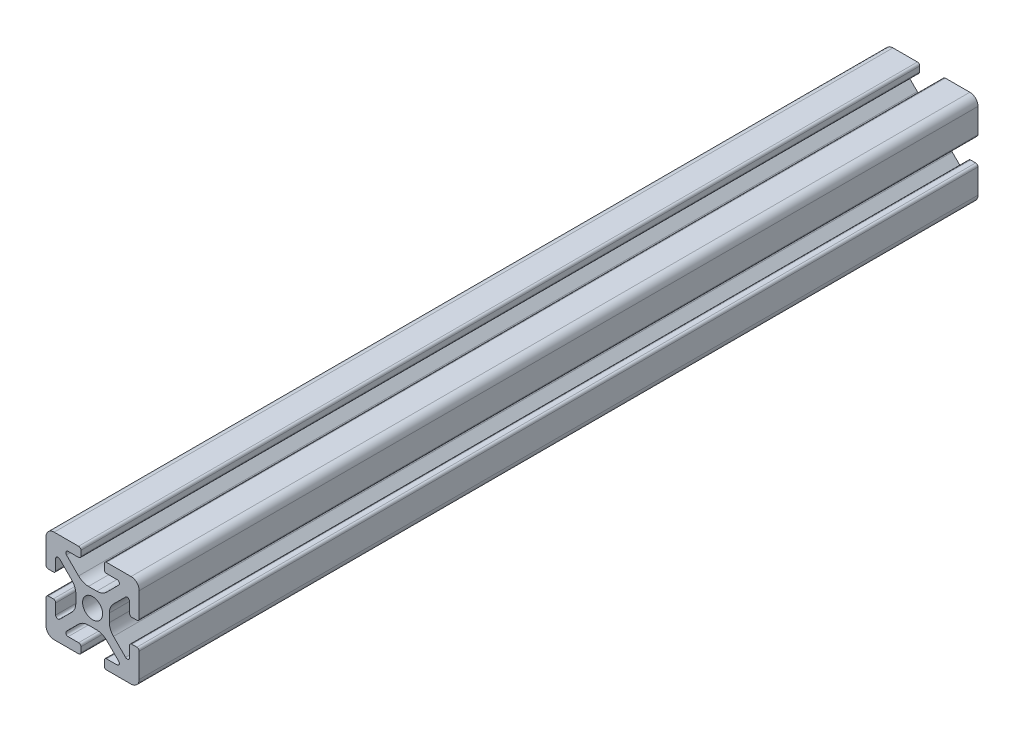
SolidWorks part; units mm, degrees
material "6063-T6"
ref_plane "Front Plane" through (0, 0, 0) normal (0, 0, 1) x (1, 0, 0)
ref_plane "Top Plane" through (0, 0, 0) normal (0, 1, 0) x (1, 0, 0)
ref_plane "Right Plane" through (0, 0, 0) normal (1, 0, 0) x (0, 0, -1)
sketch "Sketch2" plane through (0, 0, 0) normal (0, 0, 1) x (1, 0, 0)
  line L0 (0, 10) -> (0, -10) construction
  line L1 (-10, 0) -> (10, 0) construction
  line L2 (2.5, -10) -> (10, -10)
  line L3 (10, -10) -> (10, -2.5)
  line L4 (2.5, -10) -> (2.5, -7.9246)
  line L5 (2.5, -7.9246) -> (6.4571, -7.9246)
  line L6 (6.4571, -7.9246) -> (2.1325, -3.6)
  line L7 (0, 0) -> (10, -10) construction
  line L8 (10, -2.5) -> (7.9246, -2.5)
  line L9 (7.9246, -2.5) -> (7.9246, -6.4571)
  line L10 (7.9246, -6.4571) -> (3.6, -2.1325)
  line L11 (5.7623, -4.2948) -> (4.2948, -5.7623) construction
  circle A0 centre (0, 0) radius 2.15
  arc A1 (5.25, -7.9246) -> (5.6036, -7.0711) centre (5.25, -7.4246) ccw construction
  point P8 (0, -3.6)
  point P16 (5.0286, -5.0286)
  dimension "Center Hole Diameter" = 4.3
  dimension "D3" = 0.5
  dimension "Rail Height" = 20
  dimension "Rail Width" = 20
  dimension "T-Slot Width" = 5
  dimension "Slot Depth" = 6.4
  dimension "Slot Inner Width" = 11.5
sketch "Sketch3" plane through (0, 0, 0) normal (1, 0, 0) x (0, 0, -1)
  line L0 (-90, -10) -> (90, -10) construction
  line L1 (-64.6, 0) -> (64.6, 0) construction
  line L2 (0, 10) -> (0, -10) construction
  line L3 (0, 10) -> (0, -10) construction
  point P6 (-64.6, 0)
  point P8 (64.6, 0)
  dimension "Length" = 180
  dimension "D1" = 25.4
sketch "Sketch4" plane through (0, 0, 0) normal (0, 0, 1) x (1, 0, 0)
  line L0 (3, -10) -> (8.25, -10)
  line L1 (2.5, -10) -> (10, -10) construction
  line L2 (2.5, -10) -> (2.5, -7.9246) construction
  line L3 (2.5, -7.9246) -> (6.4571, -7.9246) construction
  line L4 (2.5, -8.4246) -> (2.5, -9.5)
  line L5 (3, -7.9246) -> (5.25, -7.9246)
  line L6 (0, -3.6) -> (0.8898, -3.6)
  line L7 (6.4571, -7.9246) -> (2.1325, -3.6) construction
  line L8 (3.0112, -4.4787) -> (5.6036, -7.0711)
  line L9 (10, -10) -> (10, -2.5) construction
  line L10 (7.9246, -6.4571) -> (3.6, -2.1325) construction
  line L11 (7.9246, -2.5) -> (7.9246, -6.4571) construction
  line L12 (7.9246, -5.25) -> (7.9246, -3)
  line L13 (10, -2.5) -> (7.9246, -2.5) construction
  line L14 (8.4246, -2.5) -> (9.5, -2.5)
  line L15 (10, -3) -> (10, -8.25)
  line L16 (7.0711, -5.6036) -> (4.4787, -3.0112)
  line L17 (3.6, 0) -> (3.6, -0.8898)
  line L18 (-10, 0) -> (10, 0) construction
  line L19 (0, -3.6) -> (0, -2.15)
  line L20 (0, 10) -> (0, -10) construction
  line L21 (3.6, 0) -> (2.15, 0)
  arc A0 (2.5, -9.5) -> (3, -10) centre (3, -9.5) ccw
  arc A1 (5.25, -7.9246) -> (5.6036, -7.0711) centre (5.25, -7.4246) ccw construction
  arc A2 (2.5, -8.4246) -> (3, -7.9246) centre (3, -8.4246) cw
  arc A3 (5.25, -7.9246) -> (5.6036, -7.0711) centre (5.25, -7.4246) ccw
  arc A4 (0.8898, -3.6) -> (3.0112, -4.4787) centre (0.8898, -6.6) cw
  arc A5 (8.25, -10) -> (10, -8.25) centre (8.25, -8.25) ccw
  arc A6 (7.0711, -5.6036) -> (7.9246, -5.25) centre (7.4246, -5.25) ccw
  arc A7 (7.9246, -3) -> (8.4246, -2.5) centre (8.4246, -3) cw
  arc A8 (9.5, -2.5) -> (10, -3) centre (9.5, -3) cw
  arc A9 (4.4787, -3.0112) -> (3.6, -0.8898) centre (6.6, -0.8898) cw
  circle A10 centre (0, 0) radius 2.15 construction
  arc A11 (0, -2.15) -> (2.15, 0) centre (0, 0) ccw
  dimension "D1" = 1.75
  dimension "D2" = 3
extrude "Boss-Extrude1" add sketch "Sketch4" along normal mid plane 180
mirror "Mirror1" about plane through (0, 0, 0) normal (1, 0, 0) of bodies 134
mirror "Mirror2" about plane through (0, 0, 0) normal (0, 1, 0) of bodies 135
equation "\"D3@Sketch2\"=\"T-Slot Width@Sketch2\"*0.1"
equation "\"D1@Sketch4\"=\"D3@Sketch2\"*3.5"
equation "\"D2@Sketch4\"=\"D3@Sketch2\"*6"
equation "\"D1@Boss-Extrude1\"=\"Length@Sketch3\""
